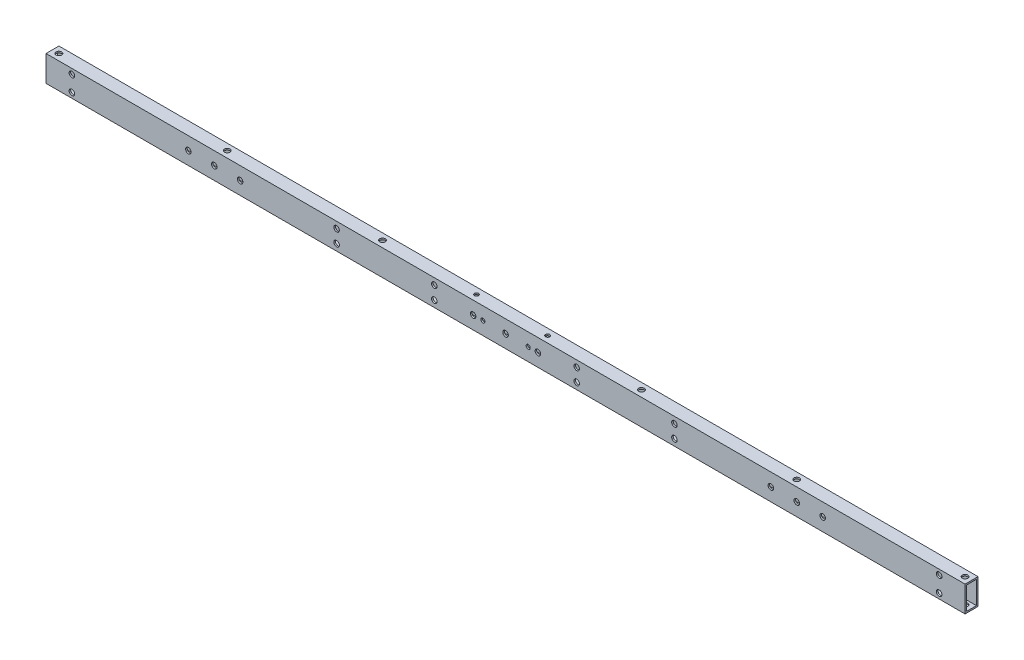
SolidWorks part; units mm, degrees
material "5052-H34"
ref_plane "正面" through (0, 0, 0) normal (0, 0, 1) x (1, 0, 0)
ref_plane "平面" through (0, 0, 0) normal (0, 1, 0) x (1, 0, 0)
ref_plane "右側面" through (0, 0, 0) normal (1, 0, 0) x (0, 0, -1)
sketch "ｽｹｯﾁ1" plane through (0, 0, 0) normal (1, 0, 0) x (0, 0, -1)
  line L1 (-5, 10) -> (5, 10)
  line L2 (-5, 10) -> (-5, -10)
  line L3 (-5, -10) -> (5, -10)
  line L4 (5, 10) -> (5, -10)
  line L5 (-5, 10) -> (5, -10) construction
  line L6 (-5, -10) -> (5, 10) construction
  point P0 (0, 0)
  dimension "D1" = 10
  dimension "D2" = 20
extrude "押し出し-薄板1" add sketch "ｽｹｯﾁ1" along normal blind 710 thin
sketch "ｽｹｯﾁ2" plane through (0, 10, 0) normal (0, 1, 0) x (1, 0, 0)
  line L0 (355, 5) -> (355, -5) construction
  line L1 (710, 5) -> (0, 5) construction
  line L2 (710, -5) -> (0, -5) construction
  line L3 (710, 0) -> (575, 0) construction
  line L4 (710, 5) -> (710, -5) construction
  line L5 (355, 0) -> (455, 0) construction
  circle A0 centre (575, 0) radius 2.15
  circle A1 centre (705, 0) radius 2.15
  circle A2 centre (5, 0) radius 2.15
  circle A3 centre (135, 0) radius 2.15
  circle A4 centre (455, 0) radius 2.15
  circle A5 centre (255, 0) radius 2.15
  circle A6 centre (420, 0) radius 2.15 construction
  circle A7 centre (290, 0) radius 2.15 construction
  circle A12 centre (382.5, 0) radius 1.6
  circle A13 centre (327.5, 0) radius 1.6
  dimension "D1" = 4.3
  dimension "D4" = 4.3
  dimension "D6" = 4.3
  dimension "D11" = 3.2
  dimension "D2" = 5
  dimension "D3" = 130
  dimension "D5" = 200
  dimension "D7" = 130
  dimension "D12" = 55
extrude "ｶｯﾄ - 押し出し1" cut sketch "ｽｹｯﾁ2" against normal through all
sketch "ｽｹｯﾁ3" plane through (0, 0, 5) normal (0, 0, 1) x (1, 0, 0)
  line L0 (355, 10) -> (355, -10) construction
  line L1 (710, 10) -> (0, 10) construction
  line L2 (710, -10) -> (0, -10) construction
  line L4 (355, 0) -> (410, 0) construction
  line L5 (410, 0) -> (410, 5) construction
  line L6 (110, 0) -> (150, 0) construction
  line L7 (710, 0) -> (690, 0) construction
  line L8 (710, 10) -> (710, -10) construction
  line L9 (690, 0) -> (690, 6) construction
  line L10 (355, 0) -> (355, 10) construction
  line L11 (300, 0) -> (300, 5) construction
  line L12 (600, 0) -> (560, 0) construction
  line L13 (0, 10) -> (0, -10) construction
  circle A3 centre (410, 5) radius 2.15
  circle A4 centre (410, -5) radius 2.15
  circle A7 centre (690, 6) radius 2.15
  circle A8 centre (690, -6) radius 2.15
  circle A9 centre (20, 6) radius 2.15
  circle A10 centre (20, -6) radius 2.15
  circle A11 centre (300, -5) radius 2.15
  circle A12 centre (300, 5) radius 2.15
  circle A19 centre (372.5, 0) radius 1.6
  circle A20 centre (337.5, 0) radius 1.6
  circle A22 centre (224.5, 5) radius 2.15
  circle A23 centre (110, 0) radius 2.15
  circle A24 centre (130, 0) radius 2.15
  circle A25 centre (150, 0) radius 2.15
  circle A26 centre (560, 0) radius 2.15
  circle A27 centre (580, 0) radius 2.15
  circle A28 centre (600, 0) radius 2.15
  circle A29 centre (224.5, -5) radius 2.15
  circle A30 centre (485.5, -5) radius 2.15
  circle A31 centre (485.5, 5) radius 2.15
  point P35 (130, 0)
  point P51 (580, 0)
  dimension "D1" = 3.2
  dimension "D4" = 4.3
  dimension "D6" = 4.3
  dimension "D11" = 40
  dimension "D9" = 4.3
  dimension "D12" = 4.3
  dimension "D10" = 224.5
  dimension "D14" = 5
  dimension "D2" = 35
  dimension "D3" = 110
  dimension "D5" = 10
  dimension "D7" = 12
  dimension "D8" = 20
  dimension "D13" = 450
extrude "ｶｯﾄ - 押し出し2" cut sketch "ｽｹｯﾁ3" against normal through all
sketch "ｽｹｯﾁ4" plane through (0, 0, 5) normal (0, 0, 1) x (1, 0, 0)
  line L0 (355, 10) -> (355, -10) construction
  line L1 (710, 10) -> (0, 10) construction
  line L2 (710, -10) -> (0, -10) construction
  line L3 (0, 0) -> (355, 0) construction
  line L4 (35, 0) -> (55, 0) construction
  line L5 (169.5, 0) -> (189.5, 0) construction
  line L6 (245, 0) -> (265, 0) construction
  circle A0 centre (35, 0) radius 6
  circle A1 centre (20, 6) radius 2.15 construction
  circle A2 centre (55, 0) radius 6
  circle A3 centre (75, 0) radius 6
  circle A4 centre (95, 0) radius 6
  circle A5 centre (169.5, 0) radius 6
  circle A8 centre (189.5, 0) radius 6
  circle A9 centre (209.5, 0) radius 6
  circle A10 centre (245, 0) radius 6
  circle A11 centre (265, 0) radius 6
  circle A12 centre (285, 0) radius 6
  circle A13 centre (320, 0) radius 6
  circle A14 centre (390, 0) radius 6
  circle A15 centre (425, 0) radius 6
  circle A16 centre (445, 0) radius 6
  circle A17 centre (465, 0) radius 6
  circle A18 centre (500.5, 0) radius 6
  circle A19 centre (520.5, 0) radius 6
  circle A20 centre (540.5, 0) radius 6
  circle A21 centre (615, 0) radius 6
  circle A22 centre (635, 0) radius 6
  circle A23 centre (655, 0) radius 6
  circle A24 centre (675, 0) radius 6
  circle A25 centre (355, 0) radius 6
  point P13 (20, 6)
  point P22 (150, 0)
  point P23 (224.5, 5)
  point P25 (110, 0)
  point P31 (300, 5)
  point P49 (337.5, 0)
  dimension "D1" = 12
  dimension "D5" = 90
  dimension "D6" = 74.5
  dimension "D2" = 15
  dimension "D4" = 20
  dimension "D7" = 19.5
  dimension "D9" = 20
  dimension "D10" = 15
  dimension "D11" = 15
  dimension "D12" = 75.5
  dimension "D14" = 20
  dimension "D15" = 20.5
  dimension "D16" = 15
  dimension "D17" = 37.5
  dimension "D18" = 20
  dimension "D3" = 4
  dimension "D8" = 3
  dimension "D13" = 3
extrude "-20g" [suppressed] cut sketch "ｽｹｯﾁ4" against normal through all
sketch "ｽｹｯﾁ5" plane through (0, 0, 5) normal (0, 0, 1) x (1, 0, 0)
  line L0 (355, 10) -> (355, -10) construction
  line L1 (710, 10) -> (0, 10) construction
  line L2 (710, -10) -> (0, -10) construction
  line L3 (355, 0) -> (380, 0) construction
  circle A0 centre (380, 0) radius 2.15
  circle A1 centre (330, 0) radius 2.15
  circle A2 centre (355, 0) radius 2.15
  dimension "D1" = 4.3
  dimension "D2" = 50
extrude "ｶｯﾄ - 押し出し3" cut sketch "ｽｹｯﾁ5" against normal through all
